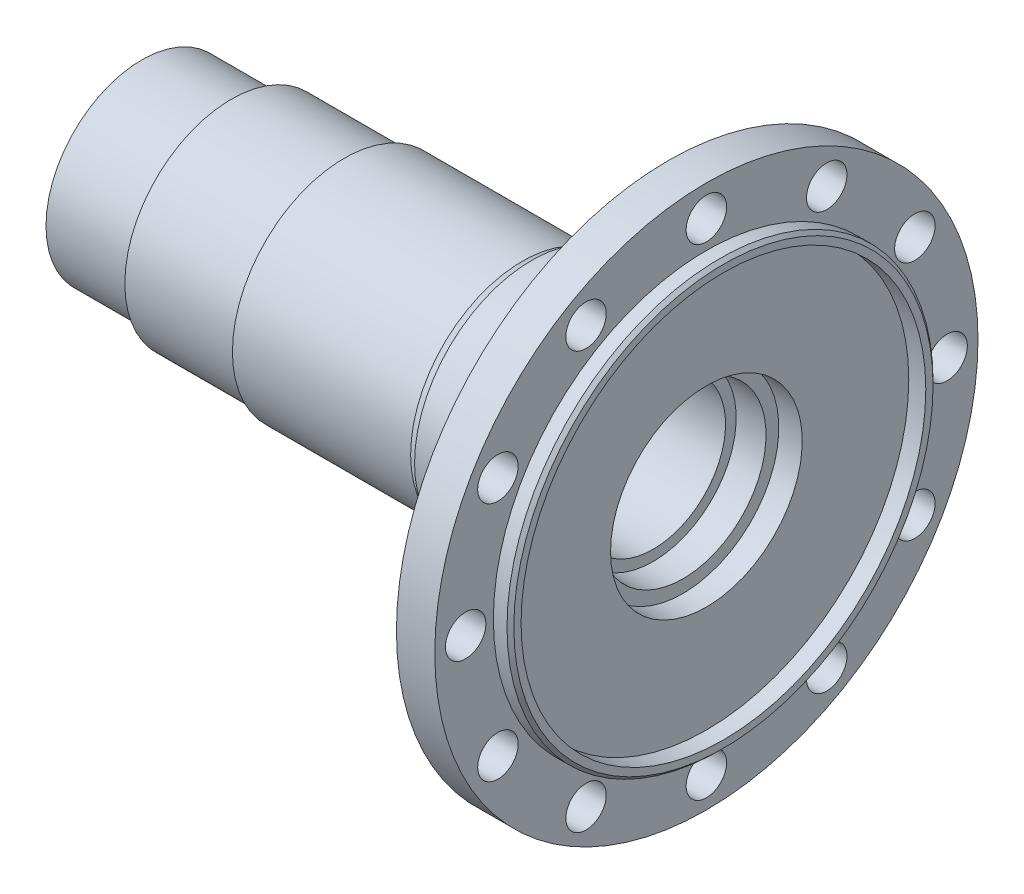
SolidWorks part; units mm, degrees
ref_plane "Спереди" through (0, 0, 0) normal (0, 0, 1) x (1, 0, 0)
ref_plane "Сверху" through (0, 0, 0) normal (0, 1, 0) x (1, 0, 0)
ref_plane "Справа" through (0, 0, 0) normal (1, 0, 0) x (0, 0, -1)
sketch "Эскиз1" plane through (0, 0, 0) normal (0, 0, 1) x (1, 0, 0)
  line L0 (0, 0) -> (273, 0)
  line L1 (0, 0) -> (0, 45)
  line L2 (0, 45) -> (42, 45)
  line L3 (42, 45) -> (42, 50)
  line L4 (42, 50) -> (95, 50)
  line L5 (95, 50) -> (95, 52.5)
  line L6 (95, 52.5) -> (178.6699, 52.5)
  line L7 (178.6699, 52.5) -> (183, 55)
  line L8 (183, 55) -> (215, 55)
  line L9 (215, 55) -> (215, 62.5)
  line L10 (215, 62.5) -> (239, 62.5)
  line L11 (239, 62.5) -> (239, 100)
  line L12 (239, 100) -> (247, 100)
  line L13 (247, 100) -> (247, 127.5)
  line L14 (247, 127.5) -> (265, 127.5)
  line L15 (265, 127.5) -> (265, 100)
  line L16 (265, 100) -> (271.4, 100)
  line L17 (271.4, 100) -> (273, 98.4)
  line L18 (273, 98.4) -> (273, 0)
revolve "Повернуть1" add sketch "Эскиз1" angle 360 about L0
sketch "Эскиз2" plane through (0, 0, 0) normal (0, 0, 1) x (1, 0, 0)
  line L0 (0, 0) -> (273, 0)
  line L1 (0, 0) -> (0, 31)
  line L2 (0, 31) -> (203.5, 31)
  line L3 (203.5, 31) -> (203.5, 34)
  line L4 (203.5, 34) -> (240, 34)
  line L5 (240, 34) -> (240, 39)
  line L6 (240, 39) -> (254, 39)
  line L7 (254, 39) -> (254, 45)
  line L8 (254, 45) -> (265, 45)
  line L9 (265, 45) -> (265, 95)
  line L10 (265, 95) -> (273, 95)
  line L11 (273, 95) -> (273, 0)
revolve "Вырез-Повернуть1" cut sketch "Эскиз2" angle 360 about L0
sketch "Эскиз3" plane through (0, 0, 0) normal (1, 0, 0) x (0, 0, -1)
  circle A0 centre (0, 113) radius 9.5
extrude "Вырез-Вытянуть1" cut sketch "Эскиз3" along normal through all
sketch "Эскиз4" plane through (0, 0, 0) normal (1, 0, 0) x (0, 0, -1)
  circle A0 centre (-56.5, 97.8609) radius 9.5
extrude "Вырез-Вытянуть2" cut sketch "Эскиз4" along normal through all
sketch "Эскиз5" plane through (0, 0, 0) normal (1, 0, 0) x (0, 0, -1)
  circle A0 centre (-97.8609, 56.5) radius 9.5
extrude "Вырез-Вытянуть3" cut sketch "Эскиз5" along normal through all
sketch "Эскиз6" plane through (0, 0, 0) normal (1, 0, 0) x (0, 0, -1)
  circle A0 centre (-113, 0) radius 9.5
extrude "Вырез-Вытянуть4" cut sketch "Эскиз6" along normal through all
sketch "Эскиз7" plane through (0, 0, 0) normal (1, 0, 0) x (0, 0, -1)
  circle A0 centre (-97.8609, -56.5) radius 9.5
extrude "Вырез-Вытянуть5" cut sketch "Эскиз7" along normal through all
sketch "Эскиз8" plane through (0, 0, 0) normal (1, 0, 0) x (0, 0, -1)
  circle A0 centre (-56.5, -97.8609) radius 9.5
extrude "Вырез-Вытянуть6" cut sketch "Эскиз8" along normal through all
sketch "Эскиз9" plane through (0, 0, 0) normal (1, 0, 0) x (0, 0, -1)
  circle A0 centre (0, -113) radius 9.5
extrude "Вырез-Вытянуть7" cut sketch "Эскиз9" along normal through all
sketch "Эскиз10" plane through (0, 0, 0) normal (1, 0, 0) x (0, 0, -1)
  circle A0 centre (56.5, -97.8609) radius 9.5
extrude "Вырез-Вытянуть8" cut sketch "Эскиз10" along normal through all
sketch "Эскиз11" plane through (0, 0, 0) normal (1, 0, 0) x (0, 0, -1)
  circle A0 centre (97.8609, -56.5) radius 9.5
extrude "Вырез-Вытянуть9" cut sketch "Эскиз11" along normal through all
sketch "Эскиз12" plane through (0, 0, 0) normal (1, 0, 0) x (0, 0, -1)
  circle A0 centre (113, 0) radius 9.5
extrude "Вырез-Вытянуть10" cut sketch "Эскиз12" along normal through all
sketch "Эскиз13" plane through (0, 0, 0) normal (1, 0, 0) x (0, 0, -1)
  circle A0 centre (97.8609, 56.5) radius 9.5
extrude "Вырез-Вытянуть11" cut sketch "Эскиз13" along normal through all
sketch "Эскиз14" plane through (0, 0, 0) normal (1, 0, 0) x (0, 0, -1)
  circle A0 centre (56.5, 97.8609) radius 9.5
extrude "Вырез-Вытянуть12" cut sketch "Эскиз14" along normal through all
